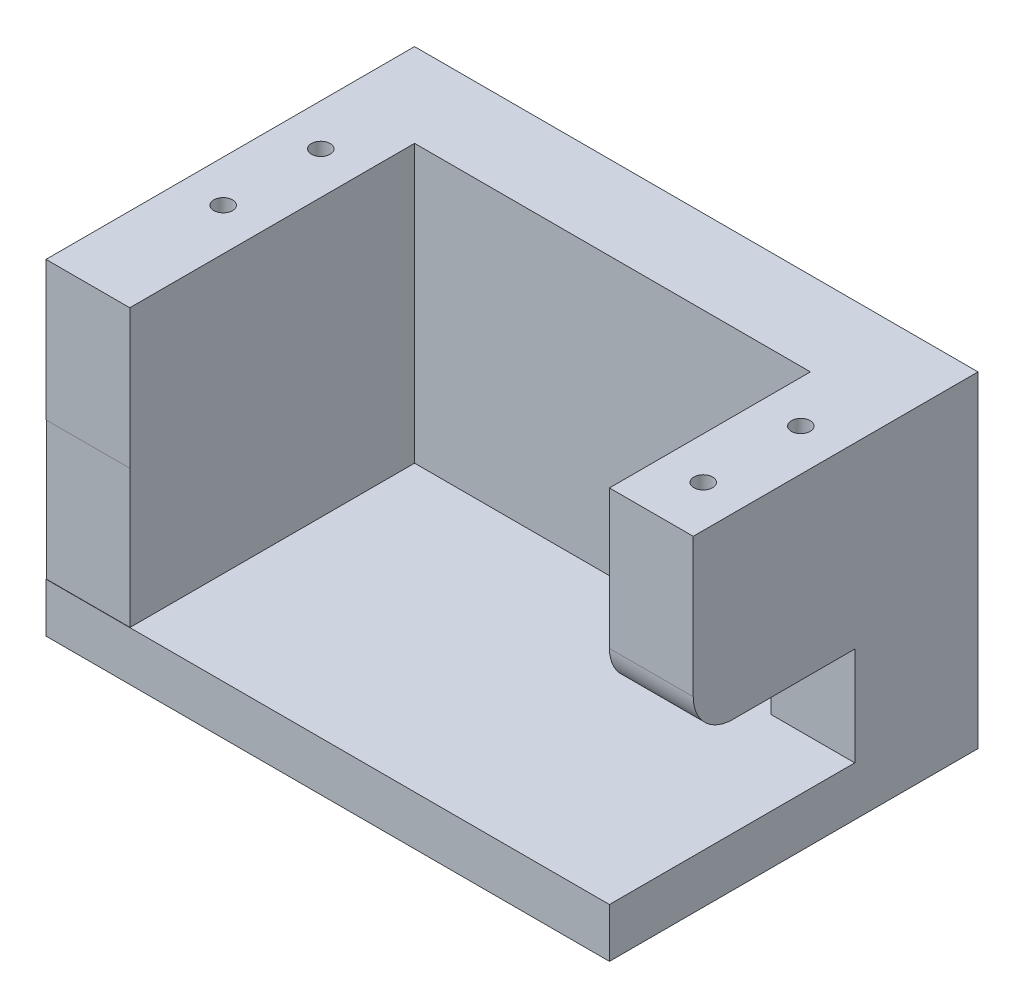
SolidWorks part; units mm, degrees
ref_plane "Front Plane" through (0, 0, 0) normal (0, 0, 1) x (1, 0, 0)
ref_plane "Top Plane" through (0, 0, 0) normal (0, 1, 0) x (1, 0, 0)
ref_plane "Right Plane" through (0, 0, 0) normal (1, 0, 0) x (0, 0, -1)
sketch "Sketch1" plane through (0, 0, 0) normal (0, 1, 0) x (1, 0, 0)
  line L0 (-28.58, -18.695) -> (28.58, -18.695)
  line L1 (-20.08, -10.195) -> (20.08, -10.195)
  line L2 (-20.08, -10.195) -> (-20.08, 10.195)
  line L3 (-20.08, 10.195) -> (20.08, 10.195)
  line L4 (20.08, -10.195) -> (20.08, 10.195)
  line L5 (-20.08, -10.195) -> (20.08, 10.195) construction
  line L6 (-20.08, 10.195) -> (20.08, -10.195) construction
  line L7 (28.58, -18.695) -> (28.58, 18.695)
  line L8 (-28.58, 18.695) -> (28.58, 18.695)
  line L9 (-28.58, -18.695) -> (-28.58, 18.695)
  point P0 (0, 0)
  dimension "D1" = 40.16
  dimension "D2" = 20.39
  dimension "D3" = 8.5
extrude "Boss-Extrude1" add sketch "Sketch1" along normal blind 5 contours L1 L4 L3 L2 | L9 L0 L7 L8 L4 L1 L2 L3
sketch "Sketch2" plane through (0, 5, 0) normal (0, 1, 0) x (1, 0, 0)
  line L4 (-20.08, -10.195) -> (20.08, -10.195)
  line L5 (20.08, -10.195) -> (20.08, 10.195)
  line L6 (20.08, 10.195) -> (-20.08, 10.195)
  line L7 (-20.08, 10.195) -> (-20.08, -10.195)
  line L8 (-20.08, -10.195) -> (20.08, -10.195)
  line L9 (20.08, -10.195) -> (20.08, 10.195)
  line L10 (20.08, 10.195) -> (-20.08, 10.195)
  line L11 (-20.08, 10.195) -> (-20.08, -10.195)
  line L12 (-28.58, -18.695) -> (28.58, -18.695)
  line L13 (28.58, -18.695) -> (28.58, 18.695)
  line L14 (28.58, 18.695) -> (-28.58, 18.695)
  line L15 (-28.58, 18.695) -> (-28.58, -18.695)
  line L16 (-28.58, -18.695) -> (28.58, -18.695) construction
  line L17 (28.58, -18.695) -> (28.58, 18.695) construction
  line L18 (28.58, 18.695) -> (-28.58, 18.695) construction
  line L19 (-28.58, 18.695) -> (-28.58, -18.695) construction
  line M9 (-28.58, 18.695) -> (-28.58, -18.695)
  line M10 (-28.58, -18.695) -> (28.58, -18.695)
  line M11 (28.58, -18.695) -> (28.58, 18.695)
  line M12 (28.58, 18.695) -> (-28.58, 18.695)
  dimension "D1" = 0
  dimension "D2" = 0
extrude "Boss-Extrude2" add sketch "Sketch2" along normal blind 28.1 contours L11 L10 L9 L8 M12 M9 M10 M11
sketch "Sketch3" plane through (0, 33.1, 0) normal (0, 1, 0) x (1, 0, 0)
  line L1 (20.08, -10.195) -> (-28.58, -10.195)
  line L2 (20.08, -10.195) -> (20.08, -18.695)
  line L3 (20.08, -18.695) -> (-28.58, -18.695)
  line L4 (-28.58, -10.195) -> (-28.58, -18.695)
extrude "Cut-Extrude1" cut sketch "Sketch3" against normal up to surface (28.1 mm away) up to face at (0, 5, 0)
sketch "Sketch5" plane through (-20.08, 0, 0) normal (1, 0, 0) x (0, 0, -1)
  line L0 (-10.195, 33.1) -> (-10.195, 5) construction
  line L1 (6.195, 5) -> (-10.195, 5)
  line L2 (6.195, 5) -> (6.195, 15)
  line L3 (6.195, 15) -> (-10.195, 15)
  line L4 (-10.195, 5) -> (-10.195, 15)
  line L5 (10.195, 33.1) -> (10.195, 5) construction
  dimension "D1" = 10
  dimension "D2" = 4
extrude "Cut-Extrude2" cut sketch "Sketch5" against normal up to next
fillet "Fillet1" radius 4 1 edges at (-24.33, 15, 10.195)
sketch "Sketch6" plane through (0, 33.1, 0) normal (0, 1, 0) x (1, 0, 0)
  line L0 (-1.9157, 0) -> (18.1643, 0) construction
  line L2 (0, 0) -> (0, 10.195) construction
  circle A0 centre (-24.35, -4.95) radius 2.25 construction
  circle A1 centre (-24.35, -4.95) radius 0.95
  circle A2 centre (-24.35, 4.95) radius 0.95
  circle A3 centre (24.35, 4.95) radius 0.95
  circle A4 centre (24.35, -4.95) radius 0.95
  dimension "D1" = 2.7
  dimension "D2" = 22.1
  dimension "D3" = 4.5
  dimension "D4" = 1.9
extrude "Cut-Extrude3" cut sketch "Sketch6" against normal blind 12
sketch "Sketch7" plane through (20.08, 0, 0) normal (-1, 0, 0) x (0, 0, 1)
  line L6 (10.195, 19) -> (10.195, 33.1)
  line L7 (-6.195, 15) -> (6.195, 15)
  line L8 (-6.195, 15) -> (6.195, 15)
  line L9 (-10.195, 5) -> (-6.195, 5)
  line L10 (-10.195, 33.1) -> (-10.195, 5)
  line L11 (10.195, 33.1) -> (-10.195, 33.1)
  line L12 (10.195, 19) -> (10.195, 33.1)
  line L15 (-10.195, 5) -> (-6.195, 5)
  line L16 (-10.195, 33.1) -> (-10.195, 5)
  line L17 (10.195, 33.1) -> (-10.195, 33.1)
  line L18 (-6.195, 5) -> (-6.195, 15)
  line L19 (-6.195, 5) -> (-6.195, 15)
  arc A1 (6.195, 15) -> (10.195, 19) centre (6.195, 19) ccw
  arc A3 (6.195, 15) -> (10.195, 19) centre (6.195, 19) ccw
  line M8 (-10.195, 5) -> (18.695, 5)
  line M9 (18.695, 5) -> (18.695, 33.1)
  line M10 (18.695, 33.1) -> (-10.195, 33.1)
  dimension "D1" = 0
extrude "Cut-Extrude4" cut sketch "Sketch7" against normal up to next contours A3 L8 L19 L12 M8 M9 M10
sketch "Sketch8" plane through (0, 33.1, 0) normal (0, 1, 0) x (1, 0, 0)
  line L0 (-20.08, -10.195) -> (-28.58, -10.195)
  line L1 (-20.08, -10.195) -> (-20.08, -18.695)
  line L2 (-28.58, -10.195) -> (-28.58, -18.695)
  line L3 (-20.08, -18.695) -> (-28.58, -18.695)
  line L4 (-20.08, -10.195) -> (-28.58, -10.195) construction
  line L5 (28.58, -18.695) -> (-28.58, -18.695) construction
extrude "Boss-Extrude3" add sketch "Sketch8" against normal up to vertex (14.1 mm away)
sketch "Sketch9" plane through (0, 5, 0) normal (0, 1, 0) x (1, 0, 0)
  line L0 (-28.58, 6.195) -> (-20.08, 6.195)
  line L1 (-28.58, 6.195) -> (-28.58, -18.6662)
  line L2 (-20.08, 6.195) -> (-20.08, -18.6662)
  line L3 (-28.58, -18.6662) -> (-20.08, -18.6662)
extrude "Boss-Extrude4" add sketch "Sketch9" along normal up to next
